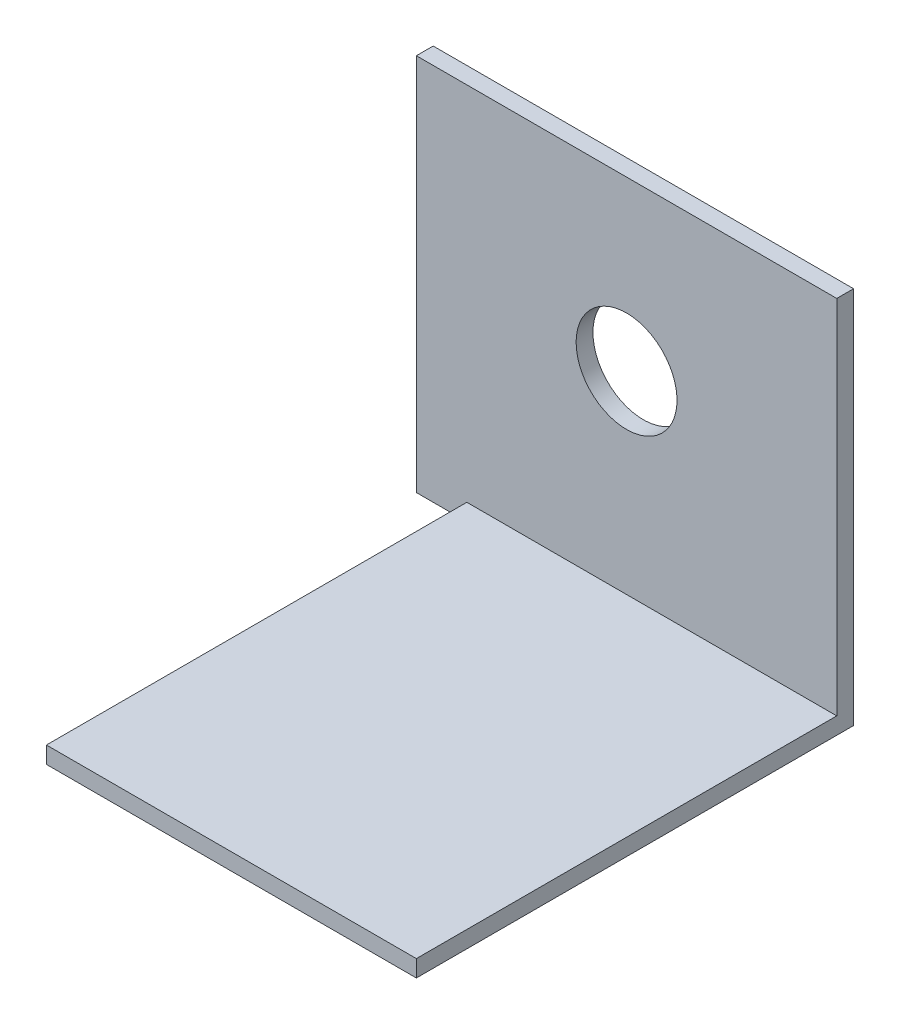
SolidWorks part; units mm, degrees
ref_plane "Front Plane" through (0, 0, 0) normal (0, 0, 1) x (1, 0, 0)
ref_plane "Top Plane" through (0, 0, 0) normal (0, 1, 0) x (1, 0, 0)
ref_plane "Right Plane" through (0, 0, 0) normal (1, 0, 0) x (0, 0, -1)
sketch "Sketch1" plane through (0, 0, 0) normal (0, 1, 0) x (1, 0, 0)
  line L1 (0, 0) -> (44, 0)
  line L2 (0, 0) -> (0, -50)
  line L3 (0, -50) -> (44, -50)
  line L4 (44, 0) -> (44, -50)
  dimension "D1" = 44
  dimension "D2" = 50
extrude "Boss-Extrude1" add sketch "Sketch1" along normal blind 2
sketch "Sketch2" plane through (0, 0, 0) normal (0, 0, -1) x (-1, 0, 0)
  line L0 (-19, 45) -> (-19, 0) construction
  line L1 (-44, 0) -> (6, 0)
  line L2 (-44, 0) -> (-44, 45)
  line L3 (-44, 45) -> (6, 45)
  line L4 (6, 0) -> (6, 45)
  circle A0 centre (-19, 25) radius 6
  dimension "D3" = 12
  dimension "D1" = 50
  dimension "D2" = 45
  dimension "D4" = 20
extrude "Boss-Extrude2" add sketch "Sketch2" along normal blind 2
